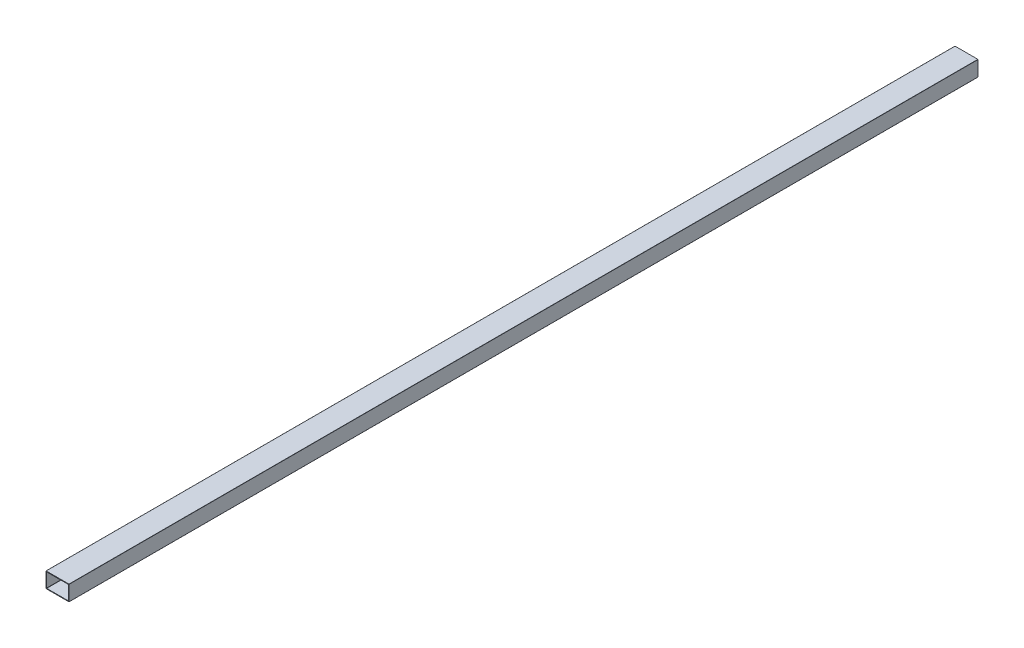
SolidWorks part; units mm, degrees
material "AISI 1035 Acero (SS)"
ref_plane "Alzado" through (0, 0, 0) normal (0, 0, 1) x (1, 0, 0)
ref_plane "Planta" through (0, 0, 0) normal (0, 1, 0) x (1, 0, 0)
ref_plane "Vista lateral" through (0, 0, 0) normal (1, 0, 0) x (0, 0, -1)
sketch "Croquis1" plane through (0, 0, 0) normal (0, 0, 1) x (1, 0, 0)
  line L0 (-72.4, -47) -> (-72.4, 47)
  line L1 (-76.2, -50.8) -> (76.2, -50.8)
  line L2 (-76.2, -50.8) -> (-76.2, 50.8)
  line L3 (-76.2, 50.8) -> (76.2, 50.8)
  line L4 (76.2, -50.8) -> (76.2, 50.8)
  line L5 (-76.2, -50.8) -> (76.2, 50.8) construction
  line L6 (-76.2, 50.8) -> (76.2, -50.8) construction
  line L7 (-72.4, 47) -> (72.4, 47)
  line L8 (72.4, -47) -> (72.4, 47)
  line L9 (-72.4, -47) -> (72.4, -47)
  point P0 (0, 0)
  dimension "D1" = 101.6
  dimension "D2" = 152.4
  dimension "D3" = 3.8
extrude "Saliente-Extruir1" add sketch "Croquis1" against normal blind 6000
fillet "Redondeo1" radius 1 8 edges at (-72.4, 47, -3000) (72.4, 47, -3000) (72.4, -47, -3000) (-76.2, -50.8, -3000) (-76.2, 50.8, -3000) (-72.4, -47, -3000) (76.2, -50.8, -3000) (76.2, 50.8, -3000)
